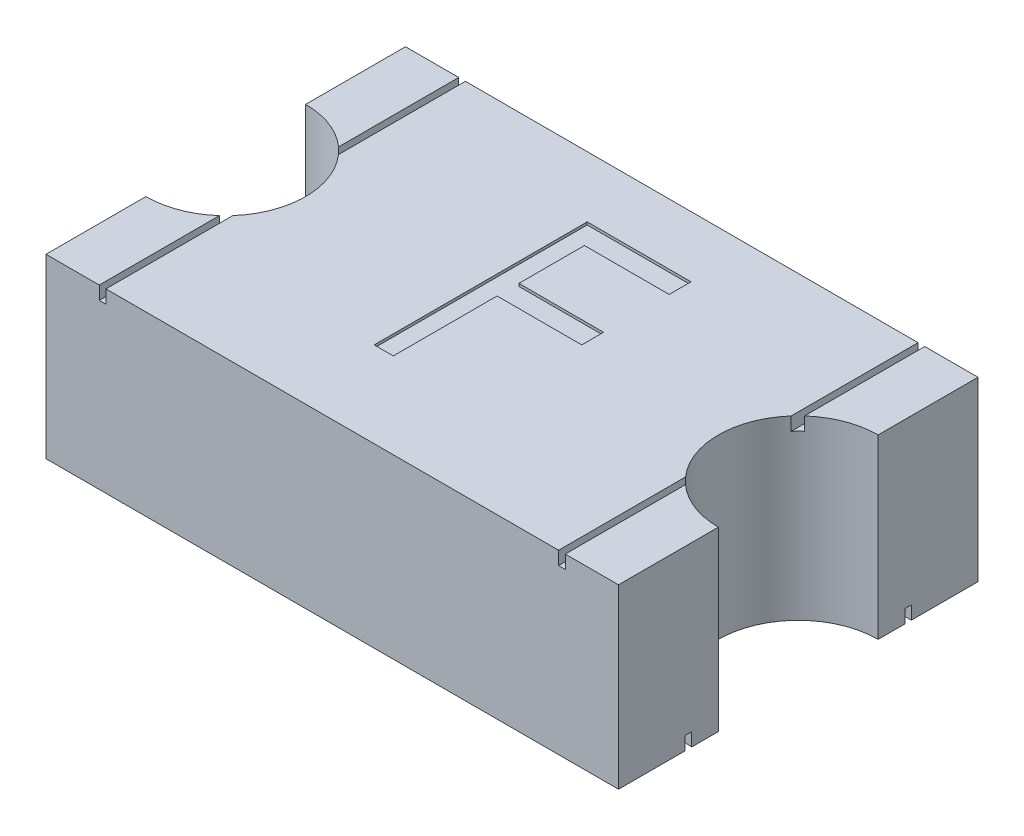
SolidWorks part; units mm, degrees
ref_plane "Front Plane" through (0, 0, 0) normal (0, 0, 1) x (1, 0, 0)
ref_plane "Top Plane" through (0, 0, 0) normal (0, 1, 0) x (1, 0, 0)
ref_plane "Right Plane" through (0, 0, 0) normal (1, 0, 0) x (0, 0, -1)
ref_plane "Plane1" through (0, 0.665, 0) normal (0, 1, 0) x (1, 0, 0)
sketch "Sketch1" plane through (0, 0.665, 0) normal (0, 1, 0) x (1, 0, 0)
  line L0 (1.075, -0.675) -> (1.075, 0.675)
  line L1 (1.075, 0.675) -> (-1.075, 0.675)
  line L2 (-1.075, 0.675) -> (-1.075, -0.675)
  line L3 (-1.075, -0.675) -> (1.075, -0.675)
extrude "Boss-Extrude1" add sketch "Sketch1" against normal blind 0.665
sketch "Sketch2" plane through (0, 0, 0.675) normal (0, 0, 1) x (1, 0, 0)
  line L0 (0.875, 0.665) -> (0.85, 0.665)
  line L1 (0.85, 0.665) -> (0.85, 0.615)
  line L2 (0.85, 0.615) -> (0.875, 0.615)
  line L3 (0.875, 0.615) -> (0.875, 0.665)
extrude "Cut-Extrude1" cut sketch "Sketch2" against normal through all
sketch "Sketch3" plane through (0, 0, 0.675) normal (0, 0, 1) x (1, 0, 0)
  line L0 (-0.85, 0.665) -> (-0.875, 0.665)
  line L1 (-0.875, 0.665) -> (-0.875, 0.615)
  line L2 (-0.875, 0.615) -> (-0.85, 0.615)
  line L3 (-0.85, 0.615) -> (-0.85, 0.665)
extrude "Cut-Extrude2" cut sketch "Sketch3" against normal through all
sketch "Sketch4" plane through (0, 0, 0) normal (0, -1, 0) x (1, 0, 0)
  line L0 (-1.075, 0.425) -> (-1.075, -0.425)
  arc A0 (-1.075, -0.425) -> (-1.075, 0.425) centre (-1.075, 0) ccw
extrude "Cut-Extrude3" cut sketch "Sketch4" against normal blind 0.05
sketch "Sketch5" plane through (0, 0.05, 0) normal (0, -1, 0) x (1, 0, 0)
  line L0 (-1.075, -0.4) -> (-1.075, 0.4)
  arc A0 (-1.075, 0.4) -> (-1.075, -0.4) centre (-1.075, 0) cw
extrude "Boss-Extrude2" add sketch "Sketch5" along normal blind 0.05
sketch "Sketch6" plane through (0, 0, 0) normal (0, -1, 0) x (1, 0, 0)
  line L0 (1.075, -0.425) -> (1.075, 0.425)
  arc A0 (1.075, 0.425) -> (1.075, -0.425) centre (1.075, 0) ccw
extrude "Cut-Extrude4" cut sketch "Sketch6" against normal blind 0.05
sketch "Sketch7" plane through (0, 0.05, 0) normal (0, -1, 0) x (1, 0, 0)
  line L0 (1.075, 0.4) -> (1.075, -0.4)
  arc A0 (1.075, -0.4) -> (1.075, 0.4) centre (1.075, 0) cw
extrude "Boss-Extrude3" add sketch "Sketch7" along normal blind 0.05
hole_wizard "Ø0.6 (0.6) Diameter Hole1" positions "Sketch9" profile "Sketch8" hole size "Ø0.6" standard "ANSI Metric"
sketch "Sketch9" plane through (0, 0, 0) normal (0, -1, 0) x (-1, 0, 0)
  point P0 (1.075, 0)
  point P1 (-1.075, 0)
sketch "Sketch8" plane through (-1.075, 0, 0) normal (1, 0, 0) x (0, 0, -1)
  line L0 (0, 0) -> (0, 0.665)
  line L1 (0, 0.665) -> (0.3, 0.665)
  line L2 (0.3, 0.665) -> (0.3, 0)
  line L5 (0.3, 0) -> (0, 0)
  line L11 (0, -6.35) -> (0, 107.95) construction
  dimension "Thru Hole Dia." = 0.6
  dimension "Thru Hole Depth" = 0.665
sketch "Sketch10" plane through (0, 0.665, 0) normal (0, 1, 0) x (1, 0, 0)
  line L0 (-0.85, -0.3535) -> (0.85, -0.3535) construction
  line L1 (-0.85, -0.1984) -> (-0.85, -0.675) construction
  line L2 (0.85, -0.1984) -> (0.85, -0.675) construction
  text T0 "F" font "Century Gothic" height 0.8
extrude "Cut-Extrude5" cut sketch "Sketch10" against normal blind 0.01
